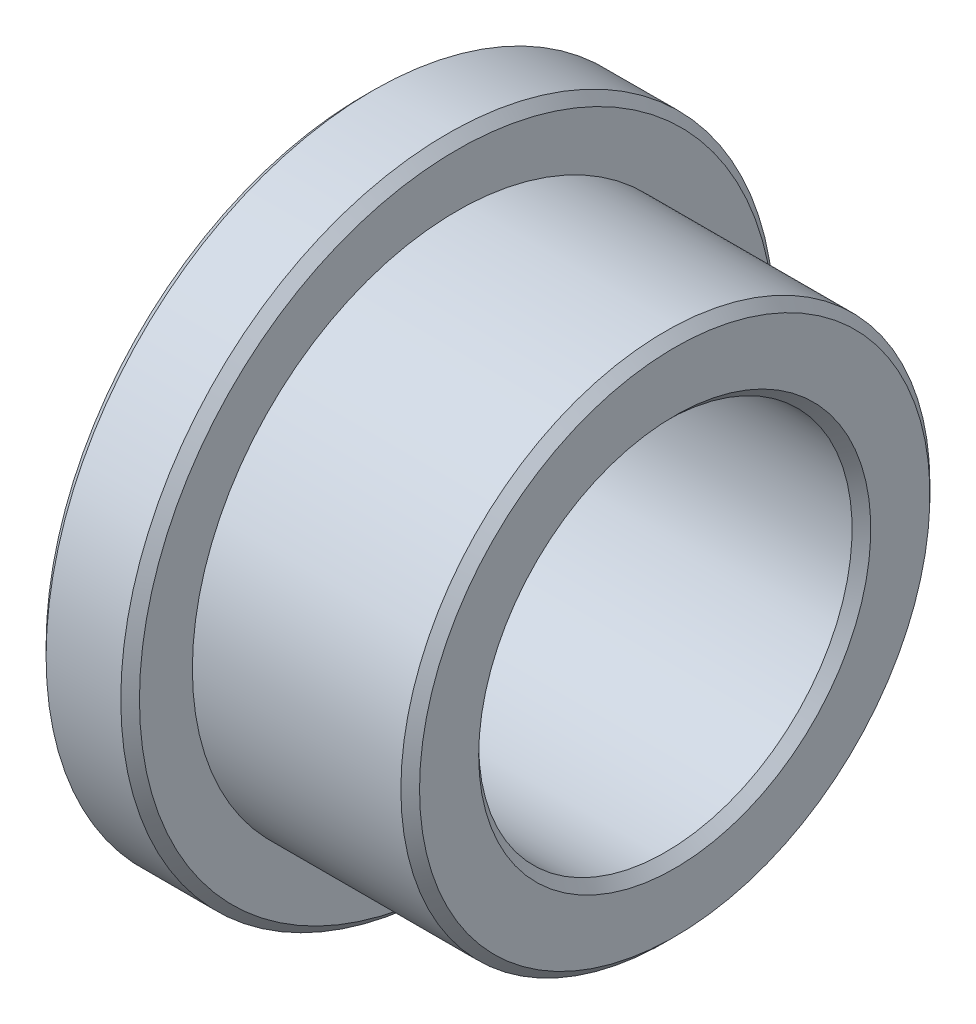
SolidWorks part; units mm, degrees
material "镀铬不锈钢"
ref_plane "前视基准面" through (0, 0, 0) normal (0, 0, 1) x (1, 0, 0)
ref_plane "上视基准面" through (0, 0, 0) normal (0, 1, 0) x (1, 0, 0)
ref_plane "右视基准面" through (0, 0, 0) normal (1, 0, 0) x (0, 0, -1)
sketch "Sketch1" plane through (0, 0, 0) normal (0, 0, 1) x (1, 0, 0)
  line L0 (0, 6) -> (0, 10.5)
  line L1 (0, 10.5) -> (3, 10.5)
  line L2 (3, 10.5) -> (3, 8.5)
  line L3 (3, 8.5) -> (10, 8.5)
  line L4 (10, 8.5) -> (10, 6)
  line L5 (10, 6) -> (0, 6)
  line L6 (0, 0) -> (24.5363, 0) construction
  dimension "D1" = 6
  dimension "D2" = 8.5
  dimension "D3" = 2
  dimension "D4" = 3
  dimension "D5" = 10
revolve "Revolve1" add sketch "Sketch1" angle 360 about L6
chamfer "Chamfer1" distance 0.3 angle 45 5 edges at (10, 0, 8.5) (0, 0, 6) (10, 0, 6) (3, 0, 10.5) (0, 0, 10.5)
